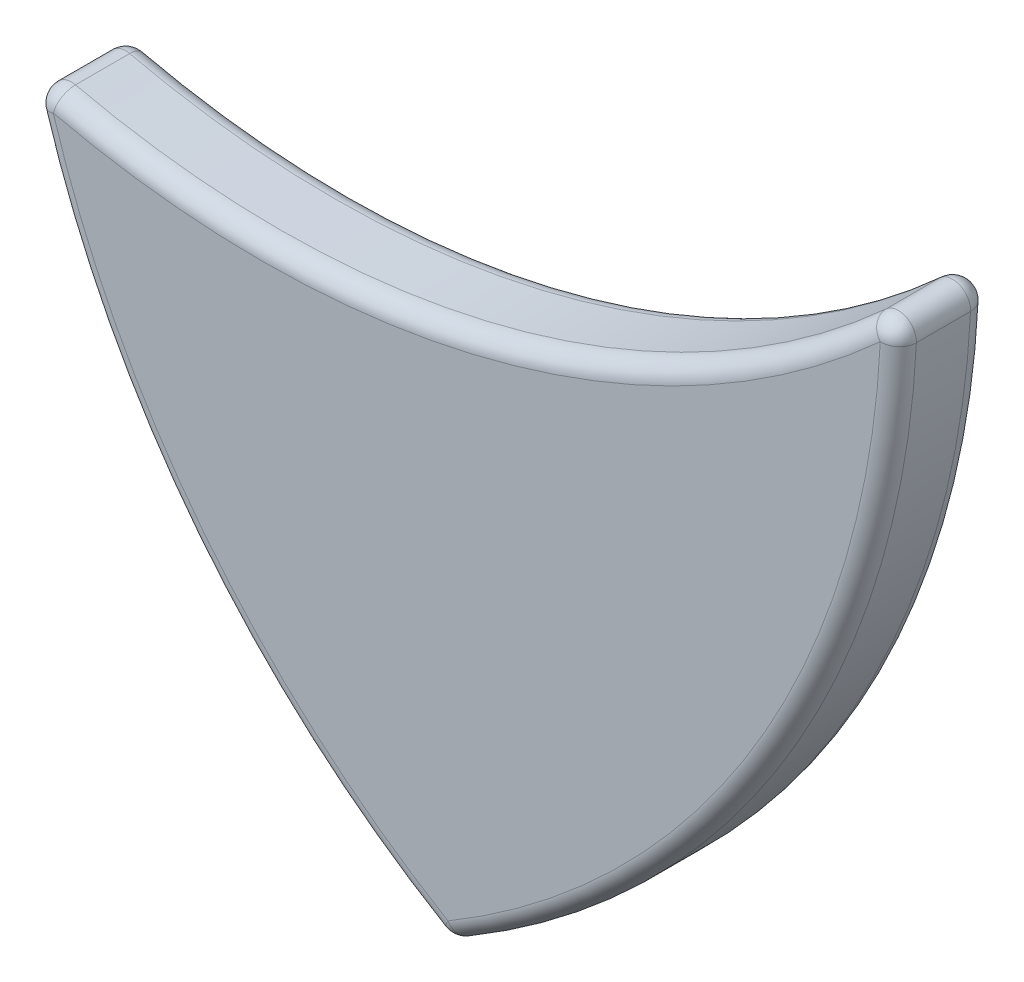
SolidWorks part; units mm, degrees
ref_plane "Piano frontale" through (0, 0, 0) normal (0, 0, 1) x (1, 0, 0)
ref_plane "Piano superiore" through (0, 0, 0) normal (0, 1, 0) x (1, 0, 0)
ref_plane "Piano destro" through (0, 0, 0) normal (1, 0, 0) x (0, 0, -1)
sketch "Schizzo1" plane through (0, 0, 0) normal (0, 0, 1) x (1, 0, 0)
  line L0 (0, 0) -> (35355.3391, 35355.3391) construction
  line L1 (0, 0) -> (35355.3391, -35355.3391) construction
  arc A0 (-48.2963, -12.941) -> (-25, -43.3013) centre (0, 0) ccw
  arc A1 (-48.2963, -12.941) -> (0, 0) centre (-35.3553, 35.3553) ccw
  arc A2 (-25, -43.3013) -> (0, 0) centre (-50, 0) ccw
  point P3 (-35.3553, 35.3553)
  point P13 (0, 0)
extrude "Estrusione-Estrusione1" add sketch "Schizzo1" along normal blind 5
fillet "Raccordo1" radius 1 9 edges at (-22.4144, -12.941, 0) (-48.2963, -12.941, 2.5) (-39.6677, -30.4381, 0) (-25, -43.3013, 2.5) (0, 0, 2.5) (-6.6987, -25, 0) (-39.6677, -30.4381, 5) (-22.4144, -12.941, 5) (-6.6987, -25, 5)
